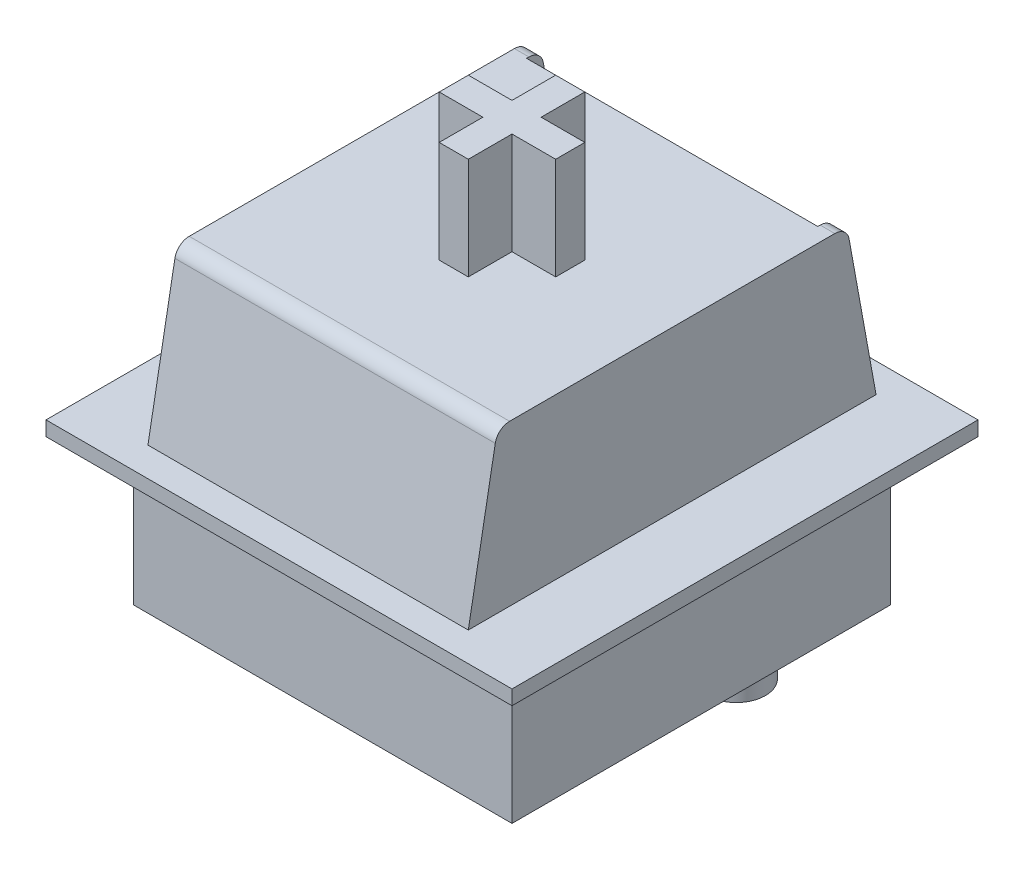
SolidWorks part; units mm, degrees
ref_plane "Front Plane" through (0, 0, 0) normal (0, 0, 1) x (1, 0, 0)
ref_plane "Top Plane" through (0, 0, 0) normal (0, 1, 0) x (1, 0, 0)
ref_plane "Right Plane" through (0, 0, 0) normal (1, 0, 0) x (0, 0, -1)
sketch "Sketch2" plane through (0, 0, 0) normal (0, 1, 0) x (1, 0, 0)
  line L1 (0, 0) -> (16, 0)
  line L2 (0, 0) -> (0, 16)
  line L3 (0, 16) -> (16, 16)
  line L4 (16, 0) -> (16, 16)
  dimension "D1" = 16
extrude "Boss-Extrude1" add sketch "Sketch2" along normal blind 11
sketch "Sketch3" plane through (0, 0, 0) normal (0, -1, 0) x (1, 0, 0)
  line L0 (8, -16) -> (8, 0) construction
  line L1 (16, -16) -> (0, -16) construction
  line L2 (0, 0) -> (16, 0) construction
  circle A0 centre (8, -8) radius 1.5
  dimension "D1" = 3
extrude "Boss-Extrude2" add sketch "Sketch3" along normal blind 3
sketch "Sketch4" plane through (0, 0, 0) normal (0, -1, 0) x (1, 0, 0)
  line L4 (1.5, -1.5) -> (1.5, -14.5)
  line L5 (1.5, -14.5) -> (14.5, -14.5)
  line L6 (14.5, -14.5) -> (14.5, -1.5)
  line L7 (14.5, -1.5) -> (1.5, -1.5)
  line L8 (0, 0) -> (0, -16)
  line L9 (0, -16) -> (16, -16)
  line L10 (16, -16) -> (16, 0)
  line L11 (16, 0) -> (0, 0)
  line L12 (0, 0) -> (0, -16)
  line L13 (0, -16) -> (16, -16)
  line L14 (16, -16) -> (16, 0)
  line L15 (16, 0) -> (0, 0)
  dimension "D1" = 0
  dimension "D2" = 1.5
extrude "Cut-Extrude1" cut sketch "Sketch4" against normal blind 5
sketch "Sketch5" plane through (0, 11, 0) normal (0, 1, 0) x (1, 0, 0)
  line L16 (7.5, 10) -> (7.5, 8.5)
  line L17 (7.5, 8.5) -> (6, 8.5)
  line L18 (6, 8.5) -> (6, 7.5)
  line L19 (0, 8) -> (16, 8) construction
  line L20 (0, 16) -> (0, 0) construction
  line L21 (16, 0) -> (16, 16) construction
  line L22 (7.5, 10) -> (8.5, 10)
  line L23 (8, 16) -> (8, 0) construction
  line L24 (16, 16) -> (0, 16) construction
  line L25 (0, 0) -> (16, 0) construction
  line L26 (7.5, 6) -> (8.5, 6)
  line L27 (7.5, 7.5) -> (6, 7.5)
  line L28 (7.5, 6) -> (7.5, 7.5)
  line L29 (8.5, 6) -> (8.5, 7.5)
  line L30 (8.5, 7.5) -> (10, 7.5)
  line L31 (10, 8.5) -> (10, 7.5)
  line L32 (8.5, 8.5) -> (10, 8.5)
  line L33 (8.5, 10) -> (8.5, 8.5)
  point P22 (6, 8)
  point P26 (8, 6)
  point P27 (8, 10)
  point P29 (10, 8)
  dimension "D1" = 4
  dimension "D2" = 4
  dimension "D3" = 1
extrude "Boss-Extrude3" add sketch "Sketch5" along normal blind 3.5
sketch "Sketch6" plane through (0, 11, 0) normal (0, 1, 0) x (1, 0, 0)
  line L4 (2.5, 13.5) -> (2.5, 2.5)
  line L5 (2.5, 2.5) -> (13.5, 2.5)
  line L6 (13.5, 2.5) -> (13.5, 13.5)
  line L7 (13.5, 13.5) -> (2.5, 13.5)
  line L8 (0, 16) -> (0, 0)
  line L9 (0, 0) -> (16, 0)
  line L10 (16, 0) -> (16, 16)
  line L11 (16, 16) -> (0, 16)
  line L12 (0, 16) -> (0, 0)
  line L13 (0, 0) -> (16, 0)
  line L14 (16, 0) -> (16, 16)
  line L15 (16, 16) -> (0, 16)
  dimension "D1" = 0
  dimension "D2" = 2.5
extrude "Cut-Extrude2" cut sketch "Sketch6" against normal blind 5.5
sketch "Sketch7" plane through (2.5, 0, 0) normal (-1, 0, 0) x (0, 0, 1)
  line L0 (-13.5, 11) -> (-13.5827, 11)
  line L1 (-14.0746, 10.5894) -> (-15, 5.5)
  line L2 (-15, 5.5) -> (-13.5, 5.5)
  line L4 (-13.5, 11) -> (-13.5, 5.5)
  line L5 (-16, 5.5) -> (-16, 5) construction
  arc A0 (-13.5827, 11) -> (-14.0746, 10.5894) centre (-13.5827, 10.5) ccw
  point P13 (-14, 11)
  dimension "D2" = 0.5
  dimension "D1" = 0.5
  dimension "D3" = 1
extrude "Boss-Extrude4" add sketch "Sketch7" against normal blind 0.5
sketch "Sketch8" plane through (13.5, 0, 0) normal (1, 0, 0) x (0, 0, -1)
  line L0 (15, 5.5) -> (13.5, 5.5) construction
  line L1 (13.5, 5.5) -> (13.5, 11) construction
  line L2 (13.5, 11) -> (13.5827, 11) construction
  line L3 (14.0746, 10.5894) -> (15, 5.5) construction
  line L12 (15, 5.5) -> (13.5, 5.5)
  line L13 (13.5, 5.5) -> (13.5, 11)
  line L14 (13.5, 11) -> (13.5827, 11)
  line L15 (14.0746, 10.5894) -> (15, 5.5)
  arc A0 (14.0746, 10.5894) -> (13.5827, 11) centre (13.5827, 10.5) ccw construction
  arc A1 (14.0746, 10.5894) -> (13.5827, 11) centre (13.5827, 10.5) ccw
extrude "Boss-Extrude5" add sketch "Sketch8" against normal blind 0.5
sketch "Sketch9" plane through (2.5, 0, 0) normal (-1, 0, 0) x (0, 0, 1)
  line L0 (-2.5, 11) -> (-2.4173, 11)
  line L1 (-1.9254, 10.5894) -> (-1, 5.5)
  line L2 (-1, 5.5) -> (-2.5, 5.5)
  line L3 (-2.5, 5.5) -> (-2.5, 11)
  line L6 (0, 5.5) -> (-16, 5.5) construction
  arc A0 (-2.4173, 11) -> (-1.9254, 10.5894) centre (-2.4173, 10.5) cw
  point P15 (-2, 11)
  dimension "D3" = 0.5
  dimension "D1" = 0.5
  dimension "D2" = 1
extrude "Boss-Extrude6" add sketch "Sketch9" against normal up to vertex (11 mm away) up to point (13.5, 11, -2.5)
sketch "Sketch10" plane through (0, 0, 0) normal (0, -1, 0) x (1, 0, 0)
  line L0 (14.5, -1.5) -> (1.5, -1.5) construction
  line L1 (1.5, -1.5) -> (1.5, -14.5) construction
  line L2 (1.5, -14.5) -> (14.5, -14.5) construction
  circle A0 centre (4.3, -10.65) radius 1
  circle A1 centre (10.55, -13.15) radius 1
  circle A2 centre (8, -8) radius 1.5
  dimension "D3" = 2
  dimension "D6" = 2
  dimension "D1" = 9.15
  dimension "D2" = 2.8
  dimension "D4" = 9.05
  dimension "D5" = 1.35
  dimension "D7" = 3.7
  dimension "D8" = 2.55
  dimension "D9" = 2.65
  dimension "D10" = 5.15
extrude "Boss-Extrude7" add sketch "Sketch10" along normal blind 3.5 contours A0 | A1
